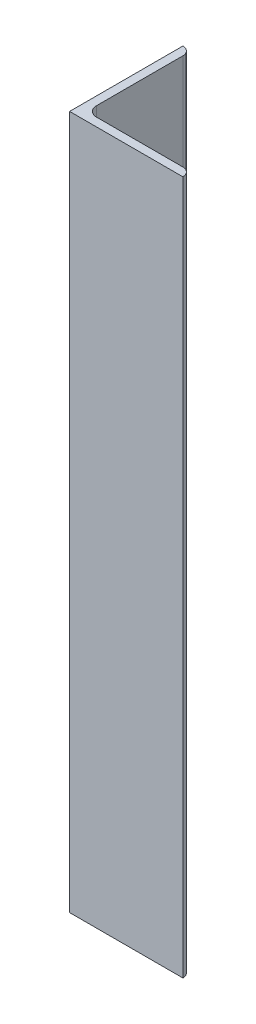
SolidWorks part; units mm, degrees
ref_plane "Front Plane" through (0, 0, 0) normal (0, 0, 1) x (1, 0, 0)
ref_plane "Top Plane" through (0, 0, 0) normal (0, 1, 0) x (1, 0, 0)
ref_plane "Right Plane" through (0, 0, 0) normal (1, 0, 0) x (0, 0, -1)
sketch3d "3DSketch1"
  line L0 (0, 0, 0) -> (0, 245, 0)
  dimension "D1" = 245
other "Iron V40X40X3(1)"
ref_plane "Plane1" through (0, 0, 0) normal (0, 1, 0) x (1, 0, 0)
sketch "Sketch1" plane through (0, 0, 0) normal (0, 1, 0) x (1, 0, 0)
  line L0 (0, 0) -> (0, 40)
  line L1 (0, 20) -> (3, 20) construction
  line L2 (3, 37) -> (3, 6.5)
  line L3 (6.5, 3) -> (37, 3)
  line L4 (20, 3) -> (20, 0) construction
  line L5 (40, 0) -> (0, 0)
  arc A0 (40, 0) -> (37, 3) centre (37, 0) ccw
  arc A1 (0, 40) -> (3, 37) centre (0, 37) cw
  arc A2 (6.5, 3) -> (3, 6.5) centre (6.5, 6.5) cw
  point P10 (20, 0)
  point P14 (0, 20)
  point P15 (3, 20)
  point P16 (20, 3)
  point P17 (3, 40)
  point P18 (40, 3)
  point P21 (0, 0)
  dimension "D2" = 3
  dimension "D3" = 40
  dimension "Radius_1" = 3.5
  dimension "D1" = 3
sketch "Sketch2" plane through (0, 0, 0) normal (-1, 0, 0) x (0, 0, 1)
  line L0 (-25.5, 100) -> (-10.5, 100) construction
  line L1 (-25.5, 105) -> (-10.5, 105)
  line L2 (-25.5, 95) -> (-10.5, 95)
  line L3 (-40, 0) -> (0, 0) construction
  line L5 (-25.5, 130) -> (-10.5, 130) construction
  line L6 (-25.5, 135) -> (-10.5, 135)
  line L7 (-25.5, 125) -> (-10.5, 125)
  line L8 (0, 0) -> (0, 245) construction
  arc A0 (-25.5, 105) -> (-25.5, 95) centre (-25.5, 100) ccw
  arc A1 (-10.5, 95) -> (-10.5, 105) centre (-10.5, 100) ccw
  arc A2 (-25.5, 135) -> (-25.5, 125) centre (-25.5, 130) ccw
  arc A3 (-10.5, 125) -> (-10.5, 135) centre (-10.5, 130) ccw
  point P2 (-18, 100)
  point P14 (-18, 130)
  dimension "D2" = 5
  dimension "D4" = 18
  dimension "D1" = 15
  dimension "D3" = 100
  dimension "D5" = 2
extrude "Cut-Extrude1" cut sketch "Sketch2" against normal blind 10
